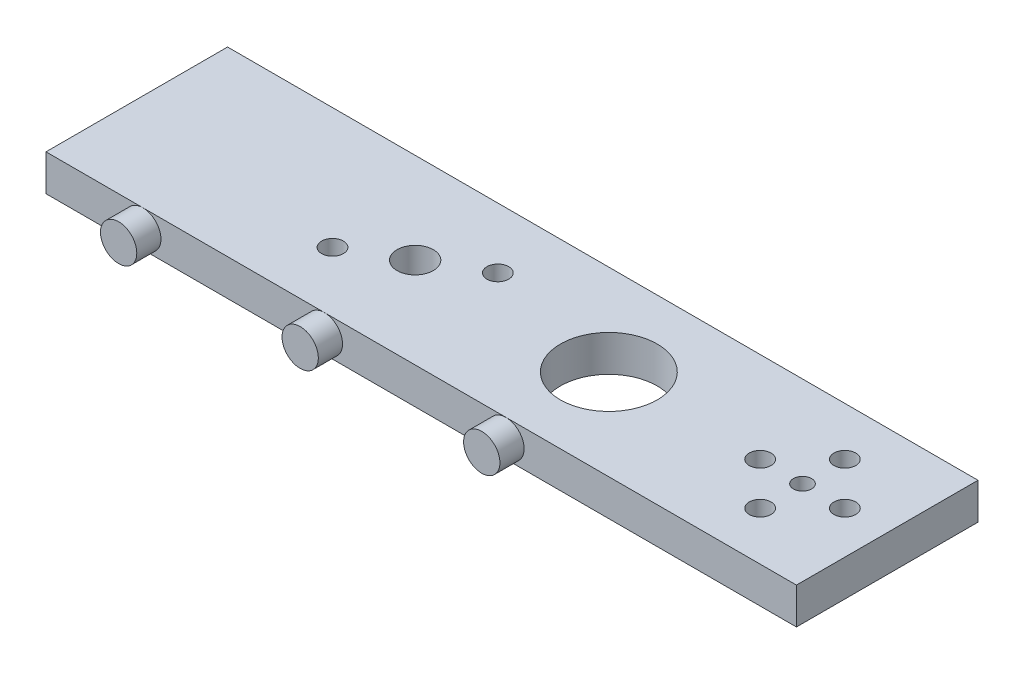
SolidWorks part; units mm, degrees
ref_plane "前视基准面" through (0, 0, 0) normal (0, 0, 1) x (1, 0, 0)
ref_plane "上视基准面" through (0, 0, 0) normal (0, 1, 0) x (1, 0, 0)
ref_plane "右视基准面" through (0, 0, 0) normal (1, 0, 0) x (0, 0, -1)
other "Configuration Table"
sketch "草图1" plane through (0, 0, 0) normal (0, 1, 0) x (1, 0, 0)
  line L0 (-31, 7.5) -> (31, 7.5)
  line L1 (31, 7.5) -> (31, -7.5)
  line L2 (31, -7.5) -> (-31, -7.5)
  line L3 (-31, -7.5) -> (-31, 7.5)
  line L4 (-31, 0) -> (31, 0) construction
  line L5 (-12.3301, -2.5) -> (-3.6699, 2.5) construction
  line L6 (-12.8083, -5.95) -> (-3.1917, -5.95) construction
  line L7 (-12.8083, 5.95) -> (-3.1917, 5.95) construction
  circle A0 centre (-8, 0) radius 1.5
  circle A1 centre (-3.6699, 2.5) radius 0.9
  circle A3 centre (-12.3301, -2.5) radius 0.9
  arc A4 (-12.8083, 5.95) -> (-12.8083, -5.95) centre (-8, 0) ccw construction
  circle A5 centre (8, 0) radius 4
  arc A6 (-3.1917, -5.95) -> (-3.1917, 5.95) centre (-8, 0) ccw construction
  circle A7 centre (24, 0) radius 0.75
  circle A8 centre (24, 0) radius 3.5 construction
  circle A9 centre (27.5, 0) radius 0.9
  circle A10 centre (24, -3.5) radius 0.9
  circle A11 centre (20.5, 0) radius 0.9
  circle A12 centre (24, 3.5) radius 0.9
  point P5 (0, 7.5)
  point P7 (-31, 0)
  dimension "D3" = 3
  dimension "D6" = 1.8
  dimension "D9" = 15.3
  dimension "D12" = 8
  dimension "D14" = 1.5
  dimension "D15" = 7
  dimension "D16" = 1.8
  dimension "D1" = 62
  dimension "D2" = 15
  dimension "D4" = 23
  dimension "D7" = 30
  dimension "D8" = 10
  dimension "D10" = 11.9
  dimension "D11" = 16
  dimension "D13" = 16
  dimension "D5" = 2
  dimension "D17" = 4
extrude "凸台-拉伸1" add sketch "草图1" along normal blind 3
sketch "草图2" plane through (0, 0, 7.5) normal (0, 0, 1) x (1, 0, 0)
  line L0 (-31, 1.5) -> (31, 1.5) construction
  line L1 (-31, 3) -> (-31, 0) construction
  line L2 (31, 3) -> (31, 0) construction
  circle A0 centre (-23, 1.5) radius 1.5
  circle A1 centre (-8, 1.5) radius 1.5
  circle A2 centre (7, 1.5) radius 1.5
  dimension "D1" = 3
  dimension "D2" = 3
  dimension "D3" = 3
  dimension "D4" = 15
  dimension "D5" = 15
  dimension "D6" = 8
extrude "凸台-拉伸2" add sketch "草图2" along normal blind 2
sketch "草图3" plane through (0, 3, 0) normal (0, 1, 0) x (1, 0, 0)
sketch "草图4" plane through (0, 3, 0) normal (0, 1, 0) x (1, 0, 0)
  text T0 "L" font "Microsoft YaHei UI" height 3.5
